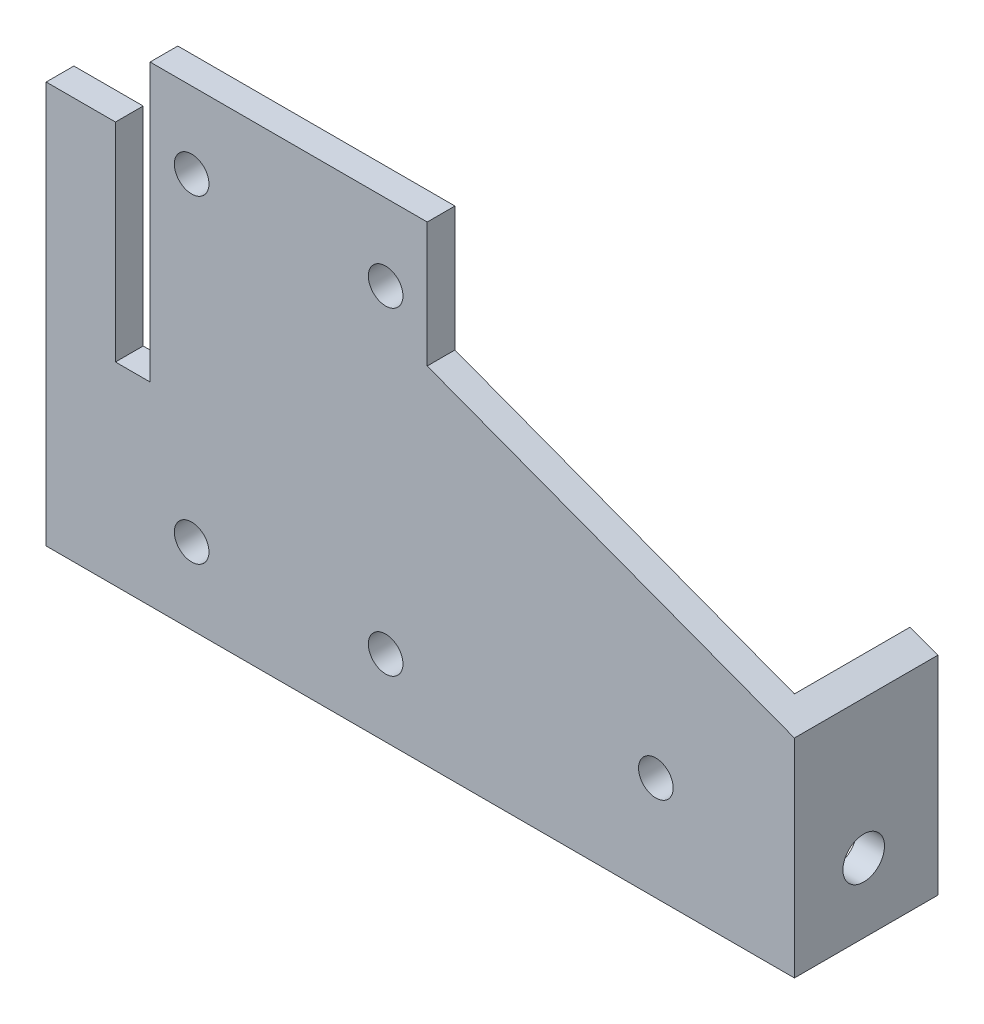
SolidWorks part; units mm, degrees
ref_plane "Спереди" through (0, 0, 0) normal (0, 0, 1) x (1, 0, 0)
ref_plane "Сверху" through (0, 0, 0) normal (0, 1, 0) x (1, 0, 0)
ref_plane "Справа" through (0, 0, 0) normal (1, 0, 0) x (0, 0, -1)
sketch "Эскиз1" plane through (0, 0, 0) normal (0, 0, 1) x (1, 0, 0)
  line L0 (35, 68) -> (35, 0) construction
  line L1 (0, 0) -> (108, 0)
  line L2 (0, 0) -> (0, 68)
  line L3 (0, 68) -> (55, 68)
  line L4 (108, 0) -> (108, 30)
  line L5 (21, 68) -> (21, 0) construction
  line L6 (55, 68) -> (55, 50)
  line L8 (49, 68) -> (49, 0) construction
  line L10 (108, 30) -> (55, 50)
  circle A0 centre (21, 57) radius 2.5
  circle A1 centre (49, 57) radius 2.5
  circle A2 centre (21, 11) radius 2.5
  circle A3 centre (49, 11) radius 2.5
  circle A4 centre (88, 15) radius 2.5
  dimension "D8" = 5
  dimension "D9" = 5
  dimension "D10" = 5
  dimension "D11" = 5
  dimension "D18" = 5
  dimension "D1" = 108
  dimension "D2" = 68
  dimension "D3" = 55
  dimension "D4" = 30
  dimension "D5" = 35
  dimension "D6" = 14
  dimension "D7" = 14
  dimension "D12" = 46
  dimension "D13" = 46
  dimension "D14" = 11
  dimension "D15" = 11
  dimension "D16" = 20
  dimension "D17" = 15
  dimension "D19" = 20
extrude "Бобышка-Вытянуть1" add sketch "Эскиз1" along normal blind 4
sketch "Эскиз2" plane through (0, 0, 4) normal (0, 0, 1) x (1, 0, 0)
  line L1 (108, 0) -> (104, 0)
  line L2 (0, 0) -> (108, 0) construction
  line L3 (104, 0) -> (104, 31.5094)
  line L4 (108, 30) -> (55, 50) construction
  line L5 (104, 31.5094) -> (108, 30)
  line L6 (108, 30) -> (108, 0)
  dimension "D1" = 4
extrude "Бобышка-Вытянуть2" add sketch "Эскиз2" against normal blind 20.7
sketch "Эскиз3" plane through (108, 0, 0) normal (1, 0, 0) x (0, 0, -1)
  line L2 (-4, 0) -> (-4, 30) construction
  line L4 (-4, 0) -> (16.7, 0) construction
  circle A0 centre (6, 10) radius 3
  dimension "D1" = 6
  dimension "D2" = 10
  dimension "D3" = 10
extrude "Вырез-Вытянуть1" cut sketch "Эскиз3" against normal blind 6.7
sketch "Эскиз4" plane through (0, 0, 0) normal (0, 0, -1) x (-1, 0, 0)
  line L1 (0, 68) -> (-15, 68)
  line L2 (0, 68) -> (0, 58)
  line L3 (0, 58) -> (-10, 58)
  line L4 (-15, 68) -> (-15, 48)
  line L6 (-15, 48) -> (-15, 28)
  line L7 (-15, 28) -> (-10, 28)
  line L8 (-10, 58) -> (-10, 28)
  dimension "D1" = 10
  dimension "D2" = 10
  dimension "D3" = 40
  dimension "D4" = 5
extrude "Вырез-Вытянуть2" cut sketch "Эскиз4" against normal blind 10
